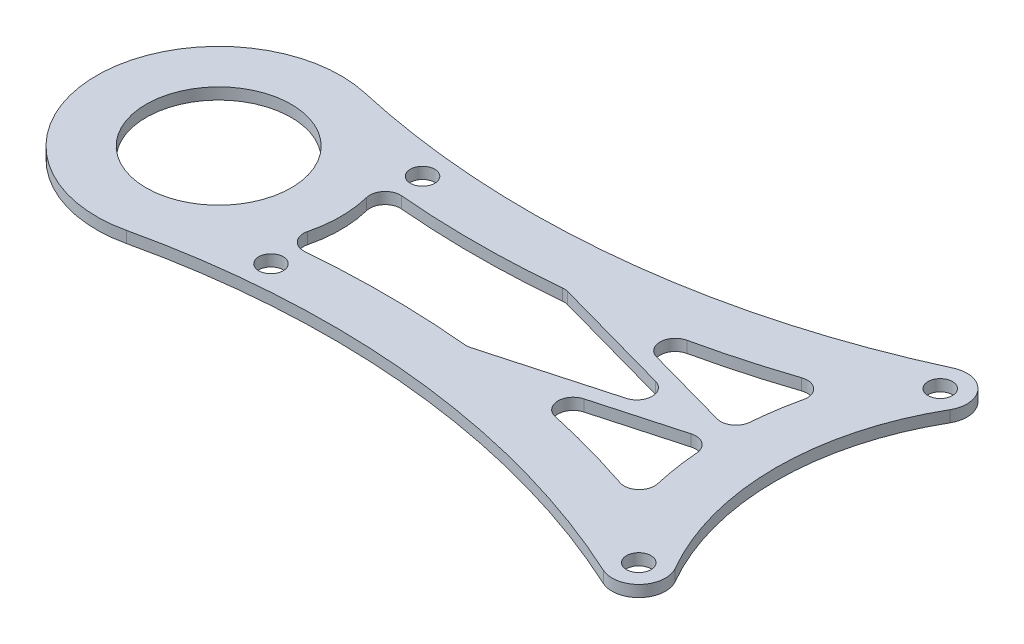
SolidWorks part; units mm, degrees
material "Thornel Mat VMA"
ref_plane "Front Plane" through (0, 0, 0) normal (0, 0, 1) x (1, 0, 0)
ref_plane "Top Plane" through (0, 0, 0) normal (0, 1, 0) x (1, 0, 0)
ref_plane "Right Plane" through (0, 0, 0) normal (1, 0, 0) x (0, 0, -1)
sketch "Sketch1" plane through (0, 0, 0) normal (0, 1, 0) x (1, 0, 0)
  line L0 (0, 0) -> (-43, 0) construction
  line L1 (0, 0) -> (-37.2391, 21.5) construction
  line L2 (0, 0) -> (-37.2391, -21.5) construction
  arc A0 (-37.2391, 21.5) -> (-37.2391, -21.5) centre (0, 0) ccw
  arc A1 (-105.4595, 15.6034) -> (-105.4595, -15.6034) centre (-109, 0) ccw
  arc A2 (-31.1769, 18) -> (-31.1769, -18) centre (0, 0) ccw
  circle A3 centre (-34.208, 19.75) radius 3.5
  circle A4 centre (-34.208, -19.75) radius 3.5
  arc A5 (-105.4595, 15.6034) -> (-35.6743, 22.928) centre (-81.3396, 121.9012) ccw
  arc A6 (-105.4595, -15.6034) -> (-35.6743, -22.928) centre (-81.3396, -121.9012) cw
  dimension "D2" = 32
  dimension "D3" = 86
  dimension "D4" = 7
  dimension "D7" = 109
  dimension "D1" = 109
  dimension "D5" = 30
  dimension "D6" = 30
  dimension "D8" = 0
extrude "Boss-Extrude1" add sketch "Sketch1" along normal mid plane 1.5 contours A1 A6 A4 A0 A3 A5 | A4 A2 A3 A0 | A4 | A3
hole_wizard "Ø3.2 (3.2) Diameter Hole1" positions "Sketch5" profile "Sketch4" hole size "Ø3.2" standard "ANSI Metric"
sketch "Sketch5" plane through (0, 0.75, 0) normal (0, 1, 0) x (1, 0, 0)
  circle A0 centre (-109, 0) radius 16
  circle A1 centre (-92.2167, 9.9283) radius 3.5
  circle A2 centre (-92.2167, -9.9283) radius 3.5
  arc A3 (-35.6743, -22.928) -> (-105.4595, -15.6034) centre (-81.3396, -121.9012) ccw construction
  arc A4 (-105.4595, 15.6034) -> (-35.6743, 22.928) centre (-81.3396, 121.9012) ccw construction
  point P0 (-34.208, 19.75)
  point P3 (-34.208, -19.75)
  point P11 (-92.2167, 9.9283)
  point P13 (-92.2167, -9.9283)
  dimension "D1" = 7
sketch "Sketch4" plane through (-34.208, 0.75, -19.75) normal (1, 0, 0) x (0, 0, 1)
  line L0 (0, 0) -> (0, 10.9614)
  line L1 (0, 10.9614) -> (1.6, 10)
  line L2 (1.6, 10) -> (1.6, 0)
  line L5 (1.6, 0) -> (0, 0)
  line L10 (0, 10.9614) -> (-1.6, 10) construction
  line L11 (0, -6.35) -> (0, 107.95) construction
  dimension "Hole Dia." = 3.2
  dimension "Hole Depth" = 10
  dimension "Drill Angle" = 118
sketch "Sketch6" plane through (0, 0.75, 0) normal (0, 1, 0) x (1, 0, 0)
  line L0 (-43, 0) -> (-67.3057, -6.7532)
  line L1 (-43, 0) -> (-67.3057, 6.7532)
  line L2 (-42.7323, 0.9635) -> (-67.038, 7.7167)
  line L3 (-43.2677, -0.9635) -> (-69.9809, 6.4586)
  line L4 (-43.2677, 0.9635) -> (-69.9809, -6.4586)
  line L5 (-42.7323, -0.9635) -> (-67.038, -7.7167)
  line L6 (-43.2677, -0.9635) -> (-67.5734, 5.7897) construction
  line L7 (-43.2677, 0.9635) -> (-67.5734, -5.7897) construction
  arc A2 (-107.0084, 8.7769) -> (-32.7417, 16.572) centre (-81.3396, 121.9012) ccw
  arc A3 (-94.4446, 6.6438) -> (-40.935, 13.1654) centre (-81.3396, 121.9012) ccw
  arc A5 (-32.7417, -16.572) -> (-107.0084, -8.7769) centre (-81.3396, -121.9012) ccw
  arc A6 (-40.935, -13.1654) -> (-94.4446, -6.6438) centre (-81.3396, -121.9012) ccw
  arc A7 (-94.4446, -6.6438) -> (-94.4446, 6.6438) centre (-109, 0) ccw
  arc A8 (-37.2391, 21.5) -> (-37.2391, -21.5) centre (0, 0) ccw
  arc A9 (-40.935, 13.1654) -> (-40.935, -13.1654) centre (0, 0) ccw
  dimension "D1" = 7
  dimension "D2" = 7
  dimension "D3" = 7
  dimension "D4" = 1
  dimension "D5" = 1
  dimension "D6" = 1
  dimension "D7" = 1
extrude "Cut-Extrude1" cut sketch "Sketch6" against normal through all contours A7 A6 L4 L3 A3 | A9 A3 L2 | A9 L5 A6
fillet "Fillet1" radius 2 11 edges at (-40.935, 0, 13.1654) (-42.9876, 0, -1.0344) (-40.935, 0, -13.1654) (-42.9876, 0, 1.0344) (-64.7797, 0, -7.0893) (-64.7797, 0, 7.0893) (-46.7355, 0, 0) (-69.9809, 0, 6.4586) (-69.9809, 0, -6.4586) (-94.4446, 0, 6.6438) (-94.4446, 0, -6.6438)
sketch "Sketch7" plane through (0, 0.75, 0) normal (0, 1, 0) x (1, 0, 0)
  circle A0 centre (-109, 0) radius 9.5
  dimension "D1" = 19
extrude "Cut-Extrude2" cut sketch "Sketch7" against normal through all
